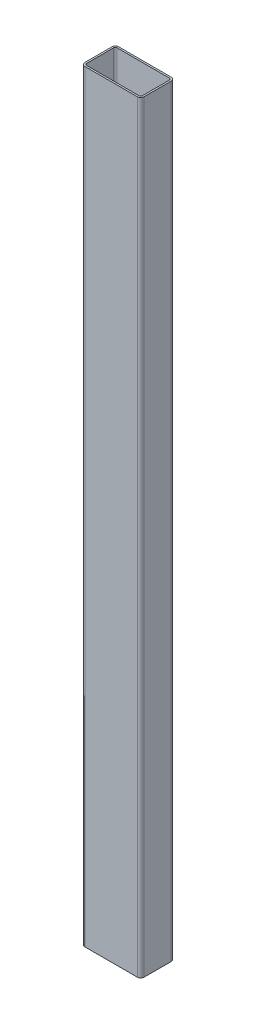
SolidWorks part; units mm, degrees
ref_plane "Plan de face" through (0, 0, 0) normal (0, 0, 1) x (1, 0, 0)
ref_plane "Plan de dessus" through (0, 0, 0) normal (0, 1, 0) x (1, 0, 0)
ref_plane "Plan de droite" through (0, 0, 0) normal (1, 0, 0) x (0, 0, -1)
sketch "Esquisse1" plane through (0, 0, 0) normal (0, 1, 0) x (1, 0, 0)
  line L0 (15.5, -9) -> (-15.5, -9)
  line L1 (15.5, -10) -> (-15.5, -10)
  line L2 (17.5, -8) -> (17.5, 8)
  line L3 (15.5, 10) -> (-15.5, 10)
  line L4 (-17.5, -8) -> (-17.5, 8)
  line L5 (17.5, -10) -> (-17.5, 10) construction
  line L6 (17.5, 10) -> (-17.5, -10) construction
  line L7 (-16.5, -8) -> (-16.5, 8)
  line L8 (15.5, 9) -> (-15.5, 9)
  line L9 (16.5, -8) -> (16.5, 8)
  arc A0 (15.5, -10) -> (17.5, -8) centre (15.5, -8) ccw
  arc A1 (-15.5, -10) -> (-17.5, -8) centre (-15.5, -8) cw
  arc A2 (17.5, 8) -> (15.5, 10) centre (15.5, 8) ccw
  arc A3 (-15.5, 10) -> (-17.5, 8) centre (-15.5, 8) ccw
  arc A4 (-15.5, -9) -> (-16.5, -8) centre (-15.5, -8) cw
  arc A5 (-15.5, 9) -> (-16.5, 8) centre (-15.5, 8) ccw
  arc A6 (16.5, 8) -> (15.5, 9) centre (15.5, 8) ccw
  arc A7 (15.5, -9) -> (16.5, -8) centre (15.5, -8) ccw
  point P0 (0, 0)
  dimension "D3" = 2
  dimension "D1" = 20
  dimension "D2" = 35
  dimension "D4" = 1
extrude "Boss.-Extru.1" add sketch "Esquisse1" along normal blind 450
